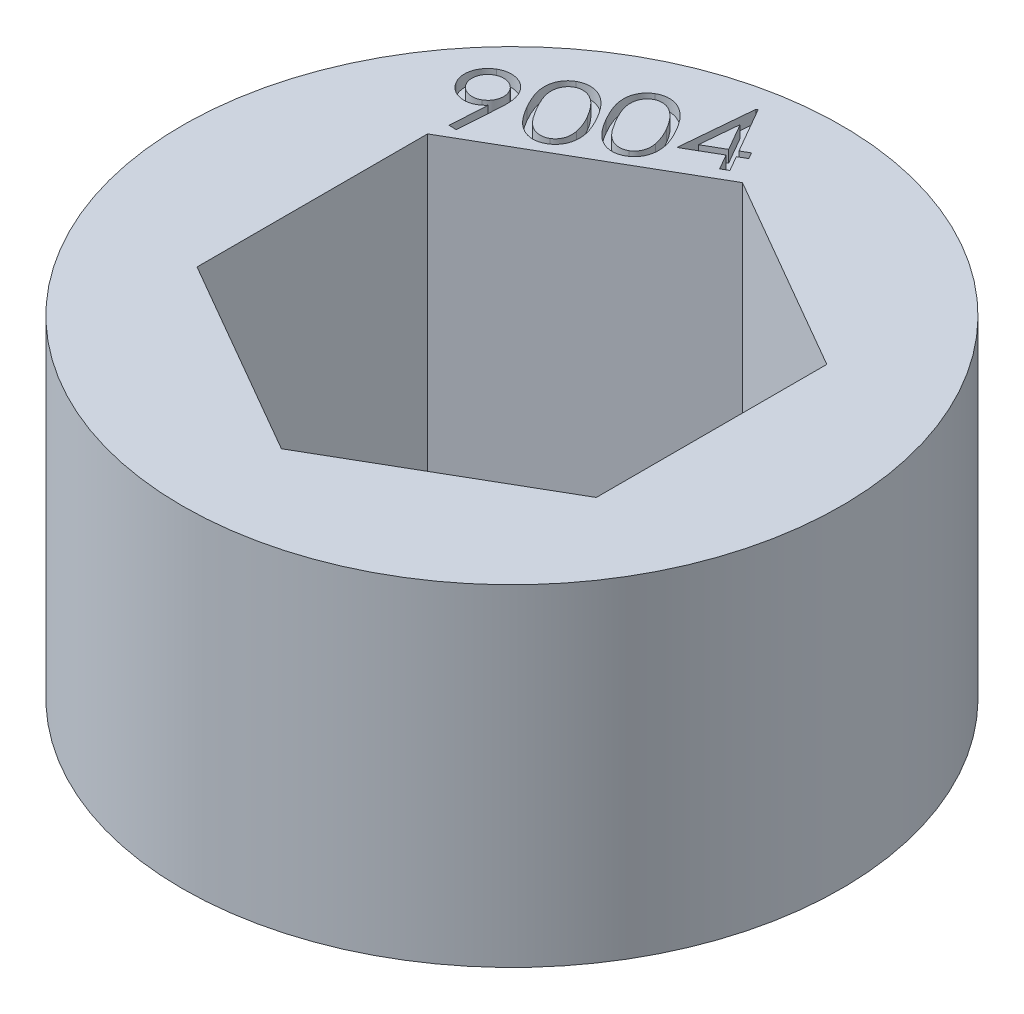
SolidWorks part; units mm, degrees
material "ABS"
ref_plane "Front Plane" through (0, 0, 0) normal (0, 0, 1) x (1, 0, 0)
ref_plane "Top Plane" through (0, 0, 0) normal (0, 1, 0) x (1, 0, 0)
ref_plane "Right Plane" through (0, 0, 0) normal (1, 0, 0) x (0, 0, -1)
sketch "Sketch1" plane through (0, 0, 0) normal (0, 1, 0) x (1, 0, 0)
  line L1 (0, 7.7723) -> (-6.731, 3.8861)
  line L2 (-6.731, 3.8861) -> (-6.731, -3.8861)
  line L3 (-6.731, -3.8861) -> (0, -7.7723)
  line L4 (0, -7.7723) -> (6.731, -3.8861)
  line L5 (6.731, -3.8861) -> (6.731, 3.8861)
  line L6 (6.731, 3.8861) -> (0, 7.7723)
  circle A0 centre (0, 0) radius 11.1125
  circle A1 centre (0, 0) radius 6.731 construction
  dimension "D1" = 22.225
  dimension "D2" = 13.462
extrude "Boss-Extrude1" add sketch "Sketch1" along normal blind 11.176
sketch "Sketch2" plane through (0, 11.176, 0) normal (0, 1, 0) x (1, 0, 0)
  line L0 (-6.9896, 4.2061) -> (-0.291, 8.0736) construction
  line L1 (0, 7.7723) -> (-6.731, 3.8861) construction
  text T0 "9004" font "Century Gothic" height 2.54
  dimension "D1" = 0.4064
extrude "Cut-Extrude1" cut sketch "Sketch2" against normal blind 0.4
